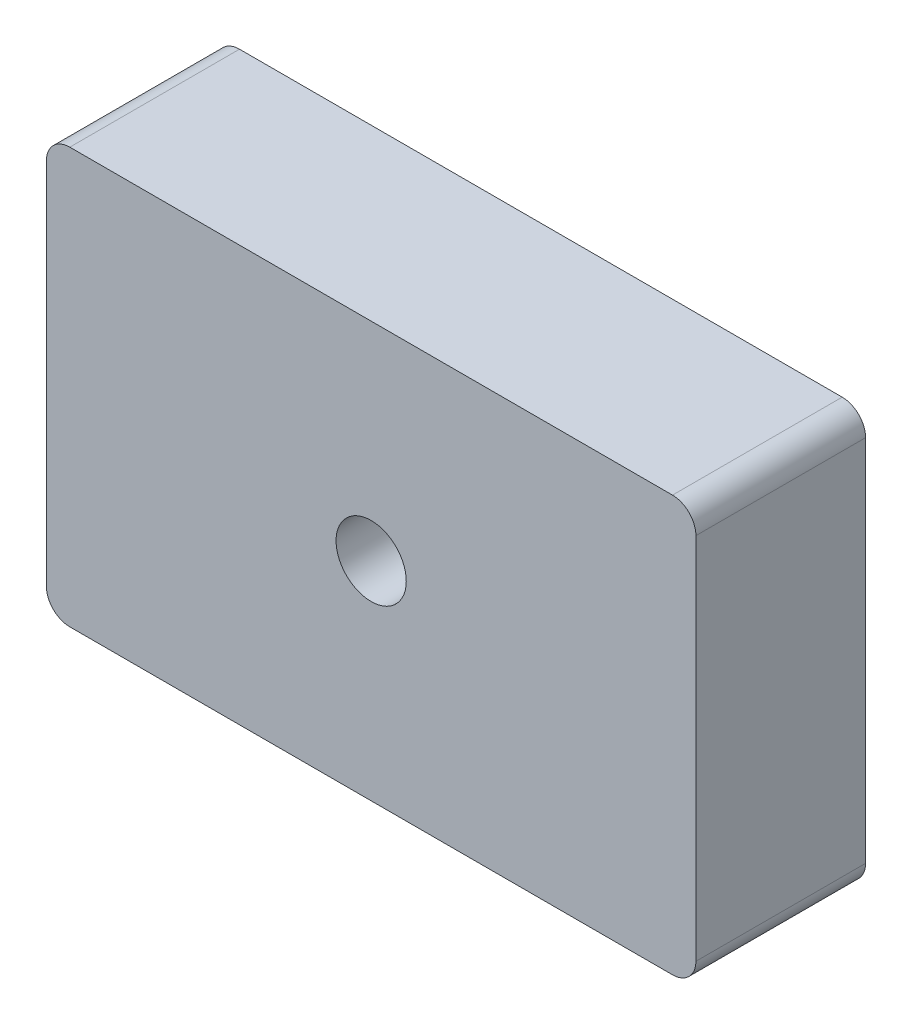
SolidWorks part; units mm, degrees
ref_plane "Front Plane" through (0, 0, 0) normal (0, 0, 1) x (1, 0, 0)
ref_plane "Top Plane" through (0, 0, 0) normal (0, 1, 0) x (1, 0, 0)
ref_plane "Right Plane" through (0, 0, 0) normal (1, 0, 0) x (0, 0, -1)
sketch "Sketch2" plane through (0, 0, 0) normal (0, 0, 1) x (1, 0, 0)
  line L1 (-35.242, -22.5425) -> (35.242, -22.5425)
  line L2 (-35.242, -22.5425) -> (-35.242, 22.5425)
  line L3 (-35.242, 22.5425) -> (35.242, 22.5425)
  line L4 (35.242, -22.5425) -> (35.242, 22.5425)
  line L5 (-35.242, -22.5425) -> (35.242, 22.5425) construction
  line L6 (-35.242, 22.5425) -> (35.242, -22.5425) construction
  point P0 (0, 0)
  dimension "D1" = 45.085
  dimension "D2" = 70.484
extrude "Boss-Extrude1" add sketch "Sketch2" along normal blind 18.415
fillet "Fillet1" radius 2.54 4 edges at (35.242, -22.5425, 9.2075) (-35.242, 22.5425, 9.2075) (35.242, 22.5425, 9.2075) (-35.242, -22.5425, 9.2075)
sketch "Sketch3" plane through (0, 0, 18.415) normal (0, 0, 1) x (1, 0, 0)
  line L0 (-35.242, 0) -> (35.242, 0) construction
  line L1 (-35.242, 20.0025) -> (-35.242, -20.0025) construction
  line L2 (35.242, -20.0025) -> (35.242, 20.0025) construction
  circle A0 centre (0, 0) radius 3.81
  point P6 (0, 0)
  dimension "D1" = 7.62
extrude "Cut-Extrude1" cut sketch "Sketch3" against normal through all
